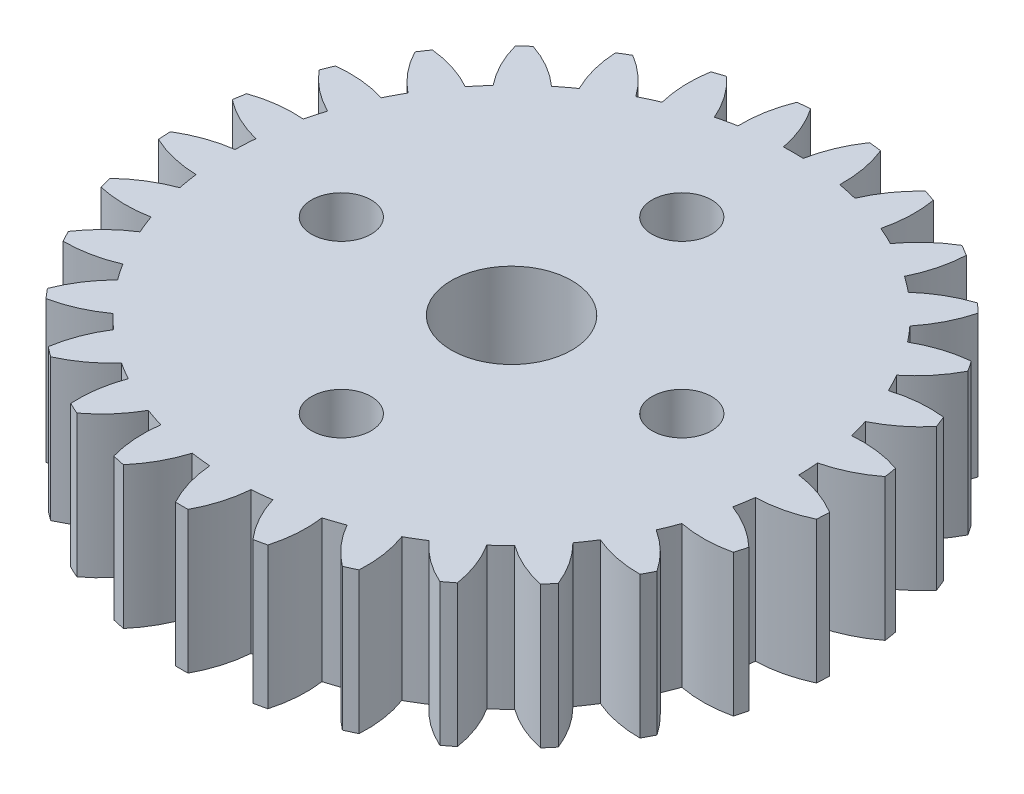
SolidWorks part; units mm, degrees
material "Acrylic (Medium-high impact)"
ref_plane "Front Plane" through (0, 0, 0) normal (0, 0, 1) x (1, 0, 0)
ref_plane "Top Plane" through (0, 0, 0) normal (0, 1, 0) x (1, 0, 0)
ref_plane "Right Plane" through (0, 0, 0) normal (1, 0, 0) x (0, 0, -1)
sketch "Sketch1" plane through (0, 0, 0) normal (0, 1, 0) x (1, 0, 0)
  circle A0 centre (0, 0) radius 23.25
  dimension "D1" = 46.5
extrude "Boss-Extrude1" add sketch "Sketch1" along normal mid plane 10
sketch "Sketch2" plane through (0, 0, 0) normal (0, 1, 0) x (1, 0, 0)
  line L0 (0, 0) -> (0, 55.6866) construction
  line L1 (0, 0) -> (-1.2702, 21.7129) construction
  line L2 (0, 0) -> (-4.6973, 43.1912) construction
  line L3 (-1.2702, 21.7129) -> (-2.3487, 21.5956) construction
  arc A0 (0.6969, 19.8618) -> (-0.6969, 19.8618) centre (0, 0) ccw
  arc A1 (2.0893, 23.1814) -> (-2.0893, 23.1814) centre (0, 0) ccw
  circle A2 centre (0, 0) radius 21.75 construction
  circle A3 centre (0, 0) radius 20.4383 construction
  arc A4 (-0.6969, 19.8618) -> (-2.0893, 23.1814) centre (-9.2423, 18.2292) ccw
  arc A5 (2.0893, 23.1814) -> (0.6969, 19.8618) centre (9.2423, 18.2292) ccw
  dimension "D1" = 39.748
  dimension "D2" = 46.5508
  dimension "D3" = 43.5
  dimension "D6" = 40.8766
  dimension "D7" = 8.7
  dimension "D4" = 6.207
  dimension "D5" = 1.0848
extrude "Cut-Extrude1" cut sketch "Sketch2" against normal through all both and the other way through all
pattern_circular "CirPattern1" count 29 over 360 about axis through (0, 0, 0) along (0, 1, 0) of "Cut-Extrude1"
sketch "Sketch3" plane through (0, 5, 0) normal (0, 1, 0) x (1, 0, 0)
  circle A0 centre (0, 0) radius 4.25
  dimension "D1" = 8.5
extrude "Cut-Extrude2" cut sketch "Sketch3" against normal through all both and the other way through all
sketch "Sketch4" plane through (0, 5, 0) normal (0, 1, 0) x (1, 0, 0)
  circle A0 centre (0, 0) radius 12 construction
  circle A1 centre (0, -12) radius 2.1
  dimension "D1" = 24
  dimension "D2" = 4.2
extrude "Cut-Extrude3" cut sketch "Sketch4" against normal through all both and the other way through all
pattern_circular "CirPattern2" count 4 over 360 about axis through (0, 0, 0) along (0, 1, 0) of "Cut-Extrude3"
sketch "Sketch5" plane through (0, 0, 0) normal (0, 1, 0) x (1, 0, 0)
  circle A0 centre (0, 0) radius 21.75 construction
  point P4 (0, 0)
  dimension "D1" = 43.5
